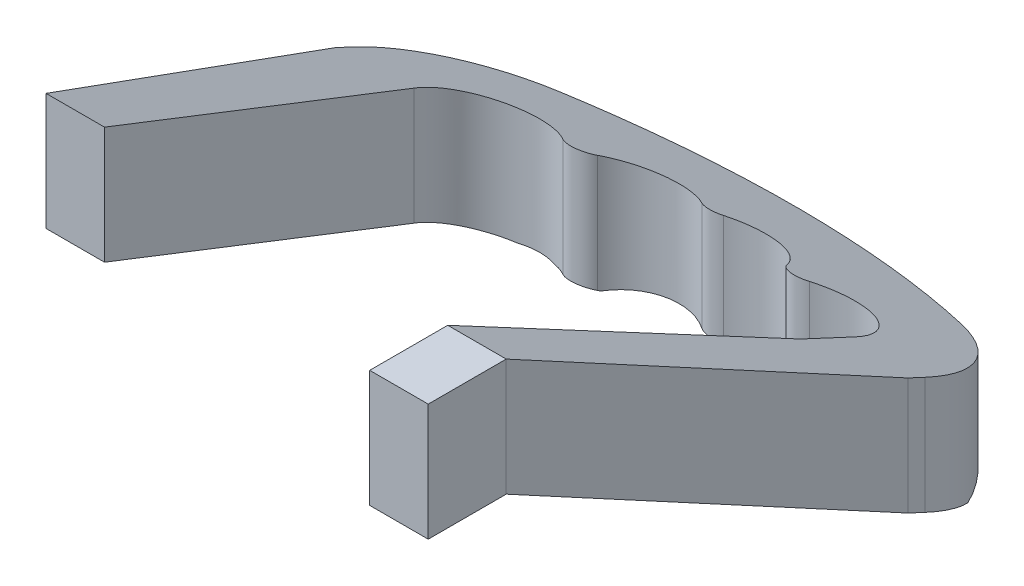
SolidWorks part; units mm, degrees
ref_plane "Front Plane" through (0, 0, 0) normal (0, 0, 1) x (1, 0, 0)
ref_plane "Top Plane" through (0, 0, 0) normal (0, 1, 0) x (1, 0, 0)
ref_plane "Right Plane" through (0, 0, 0) normal (1, 0, 0) x (0, 0, -1)
sketch "Sketch1" plane through (0, 0, 0) normal (0, 0, 1) x (1, 0, 0)
  line L4 (27.94, -4.5761) -> (37.465, -4.5761)
  line L5 (27.94, 14.4739) -> (27.94, -4.5761)
  line L6 (37.465, 14.4739) -> (27.94, 14.4739)
  line L7 (37.465, -4.5761) -> (37.465, 14.4739)
  line L8 (27.94, -4.5761) -> (37.465, -4.5761)
  line L9 (27.94, 14.4739) -> (27.94, -4.5761)
  line L10 (37.465, 14.4739) -> (27.94, 14.4739)
  line L11 (37.465, -4.5761) -> (37.465, 14.4739)
  dimension "D1" = 0
extrude "Boss-Extrude1" add sketch "Sketch1" against normal blind 12.7
sketch "Sketch2" plane through (0, 14.4739, 0) normal (0, 1, 0) x (1, 0, 0)
  line L0 (37.465, 12.7) -> (46.5828, 68.9777)
  line L1 (46.5828, 68.9777) -> (46.5828, 71.7461)
  line L2 (0, -27.94) -> (0, 27.94) construction
  line L4 (27.94, 12.7) -> (27.94, 0) construction
  line L5 (27.94, 12.7) -> (37.465, 12.7) construction
  line L6 (-35.0722, 70.2227) -> (-27.94, 12.7)
  line L7 (-46.5828, 68.9777) -> (-46.5828, 71.7461)
  line L8 (-37.465, 12.7) -> (-46.5828, 68.9777)
  line L9 (35.1948, 71.7461) -> (35.1948, 62.9058)
  line L10 (-37.465, 12.7) -> (-27.94, 12.7)
  line L11 (27.94, 12.7) -> (37.465, 12.7)
  line L12 (35.1948, 62.9058) -> (27.94, 12.7)
  arc A0 (35.1948, 71.7461) -> (20.0598, 79.4437) centre (25.6698, 71.7461) ccw
  arc A1 (15.4103, 80.475) -> (1.768, 83.7828) centre (7.0718, 75.8711) ccw
  arc A2 (-15.4103, 80.475) -> (-1.768, 83.7828) centre (-7.0718, 75.8711) cw
  arc A3 (-35.0722, 70.2227) -> (-20.0598, 79.4437) centre (-25.6698, 71.7461) cw
  arc A4 (-32.7149, 91.4367) -> (-46.5828, 71.7461) centre (-25.6698, 71.7461) ccw
  arc A5 (46.5828, 71.7461) -> (32.7149, 91.4367) centre (25.6698, 71.7461) ccw
  arc A6 (-1.768, 83.7828) -> (1.768, 83.7828) centre (0, 86.42) ccw
  arc A7 (15.4103, 80.475) -> (20.0598, 79.4437) centre (18.1898, 82.0096) ccw
  arc A8 (-15.4103, 80.475) -> (-20.0598, 79.4437) centre (-18.1898, 82.0096) cw
  arc A9 (35.1948, 67.5852) -> (-34.7723, 67.8036) centre (0, 0) ccw
  arc A10 (32.7149, 91.4367) -> (-32.7149, 91.4367) centre (0, 0) ccw
  point P34 (16.3708, 73.8086)
  point P37 (-16.3708, 73.8086)
  line M25 (37.465, 12.7) -> (27.94, 12.7)
  dimension "D1" = 19.05
  dimension "D2" = 3.175
  dimension "D3" = 3.175
  dimension "D4" = 76.2
extrude "Boss-Extrude2" add sketch "Sketch2" against normal blind 50.8 contours A5 A10 A4 L7 L8 L10 L6 A3 A8 A2 A6 A1 A7 A0 L9 L12 L0 L1 M25
sketch "Sketch3" plane through (0, 0, 0) normal (1, 0, 0) x (0, 0, -1)
  line L0 (80.7881, -36.3261) -> (12.7, -4.5761)
  line L1 (71.7461, -36.3261) -> (91.4367, -36.3261) construction
  line L2 (97.113, -24.8885) -> (12.7, 14.4739)
  line L3 (97.113, -36.3261) -> (97.113, 14.4739) construction
  line L4 (80.7881, -36.3261) -> (12.7, -36.3261)
  line L5 (12.7, -36.3261) -> (12.7, -4.5761)
  line L6 (97.113, -24.8885) -> (97.113, 14.4739)
  line L7 (97.113, 14.4739) -> (91.4367, 14.4739) construction
  line L8 (97.113, 14.4739) -> (12.7, 14.4739)
  dimension "D1" = 25
extrude "Cut-Extrude1" cut sketch "Sketch3" against normal through all both and the other way through all contours L5 L0 L4 | L8 L2 L6
